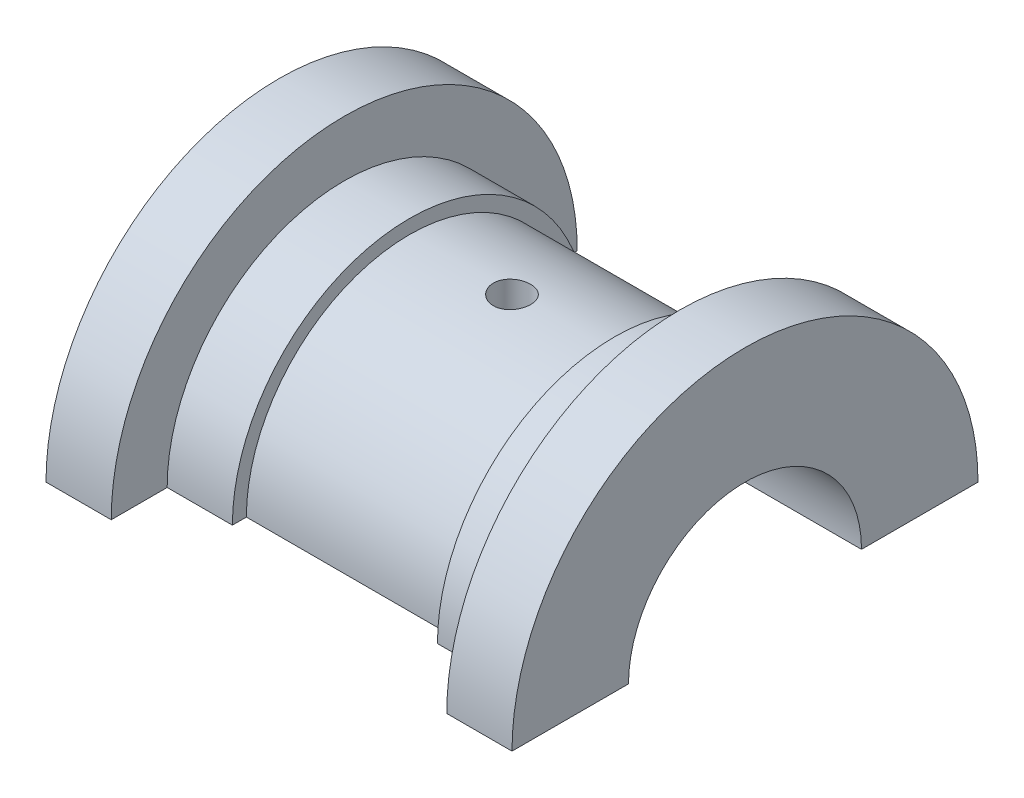
SolidWorks part; units mm, degrees
ref_plane "Front Plane" through (0, 0, 0) normal (0, 0, 1) x (1, 0, 0)
ref_plane "Top Plane" through (0, 0, 0) normal (0, 1, 0) x (1, 0, 0)
ref_plane "Right Plane" through (0, 0, 0) normal (1, 0, 0) x (0, 0, -1)
sketch "Sketch1" plane through (0, 0, 0) normal (0, 0, 1) x (1, 0, 0)
  line L0 (-25, 0) -> (25, 0)
  line L1 (25, 0) -> (25, 25)
  line L2 (25, 25) -> (18, 25)
  line L3 (18, 25) -> (18, 19)
  line L4 (18, 19) -> (11, 19)
  line L5 (11, 19) -> (11, 17.5)
  line L6 (11, 17.5) -> (-11, 17.5)
  line L8 (-11, 19) -> (-11, 17.5)
  line L9 (-18, 19) -> (-11, 19)
  line L10 (-18, 25) -> (-18, 19)
  line L11 (-25, 25) -> (-18, 25)
  line L12 (-25, 0) -> (-25, 25)
  dimension "D3" = 25
  dimension "D5" = 7
  dimension "D6" = 7
  dimension "D7" = 1.5
  dimension "D8" = 6
revolve "Revolve1" add sketch "Sketch1" angle 360 about L0
sketch "Sketch2" plane through (25, 0, 0) normal (1, 0, 0) x (0, 0, -1)
  circle A0 centre (0, 0) radius 12.5
extrude "Cut-Extrude1" cut sketch "Sketch2" against normal through all
sketch "Sketch3" plane through (25, 0, 0) normal (1, 0, 0) x (0, 0, -1)
  line L0 (-25, 0) -> (25, 0)
  circle A0 centre (0, 0) radius 25 construction
extrude "Cut-Extrude2" cut sketch "Sketch3" against normal through all and the other way through all flip side to cut
ref_plane "Plane1" through (0, 17.5, 0) normal (0, 1, 0) x (1, 0, 0)
sketch "Sketch4" plane through (0, 17.5, 0) normal (0, 1, 0) x (1, 0, 0)
  circle A0 centre (0, 0) radius 2
extrude "Cut-Extrude3" cut sketch "Sketch4" against normal through all
